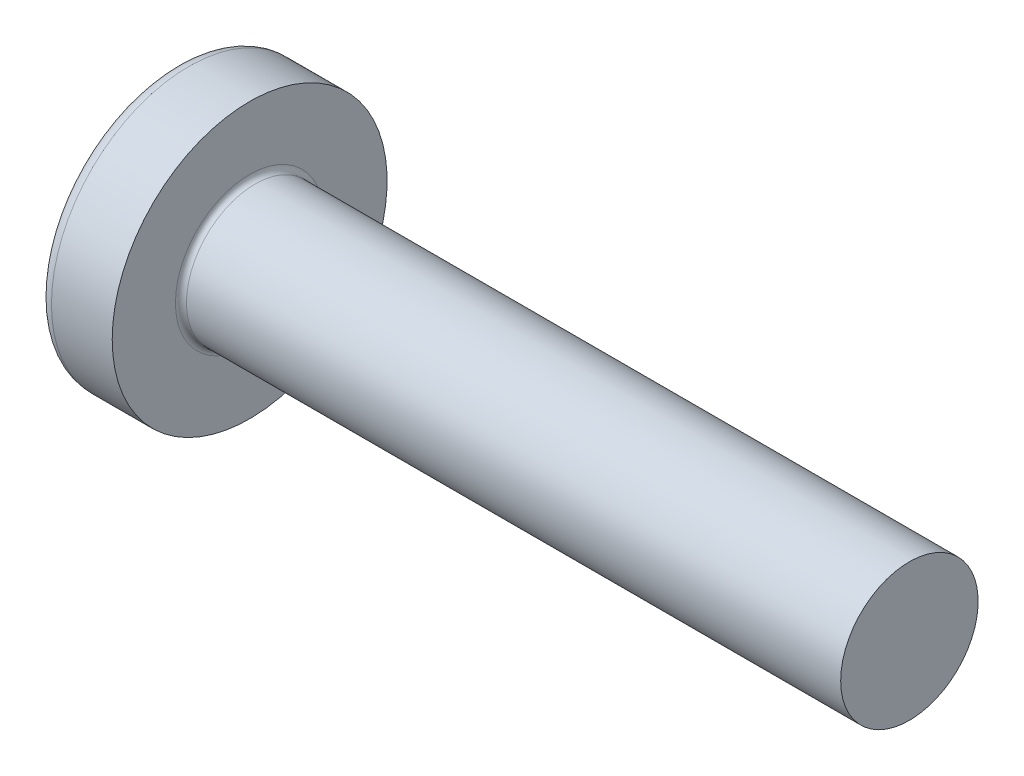
SolidWorks part; units mm, degrees
ref_plane "Plane1" through (0, 0, 0) normal (0, 0, 1) x (1, 0, 0)
ref_plane "Plane2" through (0, 0, 0) normal (0, 1, 0) x (1, 0, 0)
ref_plane "Plane3" through (0, 0, 0) normal (1, 0, 0) x (0, 0, -1)
sketch "BodySke" plane through (0, 0, 0) normal (0, 0, 1) x (1, 0, 0)
  line L0 (2.1, 1.25) -> (2.1, 2.5)
  line L1 (2.325, 6.35) -> (2.325, -3.175) construction
  line L2 (-25.4, 0) -> (127, 0) construction
  line L3 (14.1, 0) -> (0, 0)
  line L4 (2.1, 1.25) -> (14.1, 1.25)
  line L5 (14.1, 1.25) -> (14.1, 0)
  line L6 (0.995, 2.5) -> (2.1, 2.5)
  line L8 (2.1, 6.35) -> (2.1, -3.175) construction
  arc A0 (0.8032, 2.4043) -> (0, 0) centre (4, 0) ccw
  arc A2 (0.8032, 2.4043) -> (0.995, 2.5) centre (0.995, 2.26) cw
  dimension "Head_fillet_rad" = 0.24
  dimension "Head_crown_rad" = 4
  dimension "Head_ht" = 2.1
  dimension "Diameter" = 2.5
  dimension "Length" = 12
  dimension "Head_dia" = 5
  dimension "Advance" = 0.45
  dimension "Thread_nom" = 12
revolve "Base-Revolve" add sketch "BodySke"
cosmetic thread "ThreadCosmetic" [suppressed]
fillet "Fillet1" radius 0.1 1 edges at (2.1, 0, 1.25)
sketch "Sketch3" plane through (0, 0, 0) normal (1, 0, 0) x (0, 0, -1)
  line L0 (0.37, -1.3) -> (-0.37, -1.3)
  line L1 (0.37, -1.3) -> (0.37, 1.3)
  line L2 (-0.37, 1.3) -> (0.37, 1.3)
  line L3 (-0.37, 1.3) -> (-0.37, -1.3)
  dimension "D1" = 1.3
  dimension "Cross_dia" = 2.6
  dimension "D2" = 0.37
  dimension "Cross_width" = 0.74
ref_plane "Plane4" through (1.5, 0, 0) normal (1, 0, 0) x (0, 0, -1)
sketch "Sketch4" plane through (1.5, 0, 0) normal (1, 0, 0) x (0, 0, -1)
  line L0 (0.37, -0.5521) -> (-0.37, -0.5521)
  line L1 (0.37, -0.5521) -> (0.37, 0.5521)
  line L2 (-0.37, 0.5521) -> (0.37, 0.5521)
  line L3 (-0.37, 0.5521) -> (-0.37, -0.5521)
  dimension "D1" = 0.74
  dimension "D2" = 1.1043
  dimension "D3" = 0.37
  dimension "D4" = 0.5521
loft "Recess" cut profiles "Sketch3", "Sketch4"
pattern_circular "RecPat" count 2 every 90 about axis through (0, 0, 0) along (1, 0, 0) of "Recess"
sketch "RecCorSke" plane through (0, 0, 0) normal (0, 0, 1) x (1, 0, 0)
  line L0 (-3.175, 0) -> (15.875, 0) construction
  line L1 (-25.4, 0) -> (127, 0) construction
  line L2 (0, 0) -> (0, 0.6609)
  line L3 (0, 0.6609) -> (1.5, 0.556)
  line L4 (1.5, 0.556) -> (1.6807, 0)
  line L5 (1.6807, 0) -> (0, 0)
  dimension "Diameter" = 1.112
  dimension "Depth" = 1.5
  dimension "Draft_angle" = 4
  dimension "Bottom_angle" = 18
revolve "RecessCore" cut sketch "RecCorSke" angle 360 about L0
sketch "ThdSchSke" plane through (0, 0, 0) normal (0, 0, 1) x (1, 0, 0)
  line L0 (3, -0.9965) -> (2.8225, -1.25)
  line L1 (3, -0.9965) -> (3.1775, -1.25)
  line L2 (3.1775, -1.25) -> (3.1775, -1.5625)
  line L3 (-3.175, 0) -> (5.1513, 0) construction
  line L5 (3.1775, -1.5625) -> (2.8225, -1.5625)
  line L6 (2.8225, -1.5625) -> (2.8225, -1.25)
  dimension "Thread_minor" = 1.993
  dimension "Diameter" = 2.5
  dimension "Start" = 3
  dimension "SideAngle" = 55
  dimension "VeeAngle" = 70
  dimension "Overcut" = 3.125
revolve "ThreadSchematic" [suppressed] cut sketch "ThdSchSke" angle 360 about L3
pattern_linear "ThdSchPat" [suppressed]
equation "\"D1@Sketch3\" = \"Cross_dia@Sketch3\" / 2"
equation "\"D2@Sketch3\" = \"Cross_width@Sketch3\" / 2"
equation "\"Depth@RecCorSke\" = \"Cross_depth@Plane4\""
equation "\"D1@Sketch4\" = \"Cross_width@Sketch3\""
equation "\"D2@Sketch4\" = \"Cross_dia@Sketch3\" - 2.0 * \"Cross_depth@Plane4\" * tan(26.5  * 0.017453292)"
equation "\"D3@Sketch4\" = \"D1@Sketch4\" / 2"
equation "\"D4@Sketch4\" = \"D2@Sketch4\" / 2"
equation "\"Thread_length@ThreadCosmetic\" = ((sgn( (\"Length@BodySke\" - \"Advance@BodySke\" * 2.0 ) - \"Thread_nom@BodySke\" )-1)*( (\"Length@BodySke\" - \"Advance@BodySke\" * 2.0 ) - \"Thread_nom@BodySke\" ))/-2+ \"Thread_nom@BodySke\""
equation "\"Thread_minor@ThdSchSke\" = \"Thread_minor@ThreadCosmetic\""
equation "\"Diameter@ThdSchSke\" = \"Diameter@BodySke\""
equation "\"Overcut@ThdSchSke\" = \"Diameter@BodySke\" * 1.25"
equation "\"Start@ThdSchSke\" = \"Head_ht@BodySke\" + \"Length@BodySke\" - \"Thread_length@ThreadCosmetic\"  '---Non-countersunk---"
equation "\"Num_threads@ThdSchPat\" = int( \"Thread_length@ThreadCosmetic\" / \"Advance@BodySke\" + 0.999 )  + 1"
equation "\"Advance@ThdSchPat\" = \"Thread_length@ThreadCosmetic\" /  (\"Num_threads@ThdSchPat\" - 1) 'relax it"
